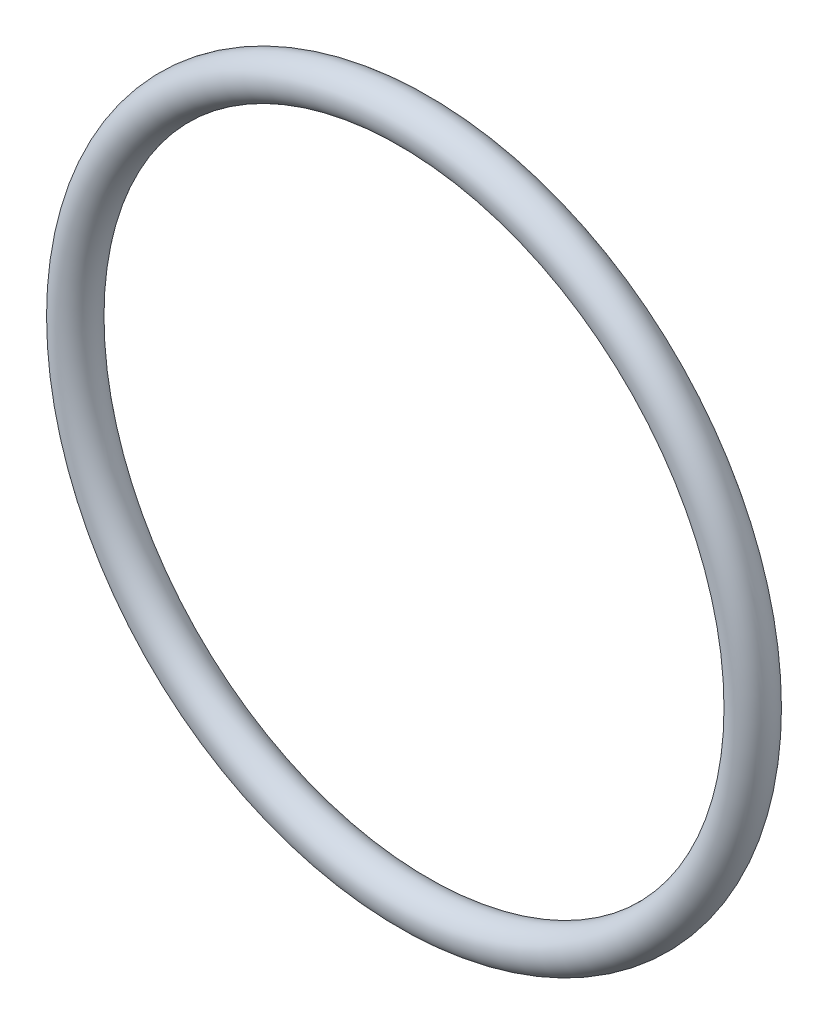
SolidWorks part; units mm, degrees
material "Silicon Rubber"
ref_plane "Front Plane" through (0, 0, 0) normal (0, 0, 1) x (1, 0, 0)
ref_plane "Top Plane" through (0, 0, 0) normal (0, 1, 0) x (1, 0, 0)
ref_plane "Right Plane" through (0, 0, 0) normal (1, 0, 0) x (0, 0, -1)
sketch "Sketch1" plane through (0, 0, 0) normal (0, 0, 1) x (1, 0, 0)
  circle A0 centre (0, 0) radius 25.4
  dimension "D1" = 50.8
sweep "Sweep1" add path "Sketch1" circular profile diameter 3.048 parameters "D3"=3.048
